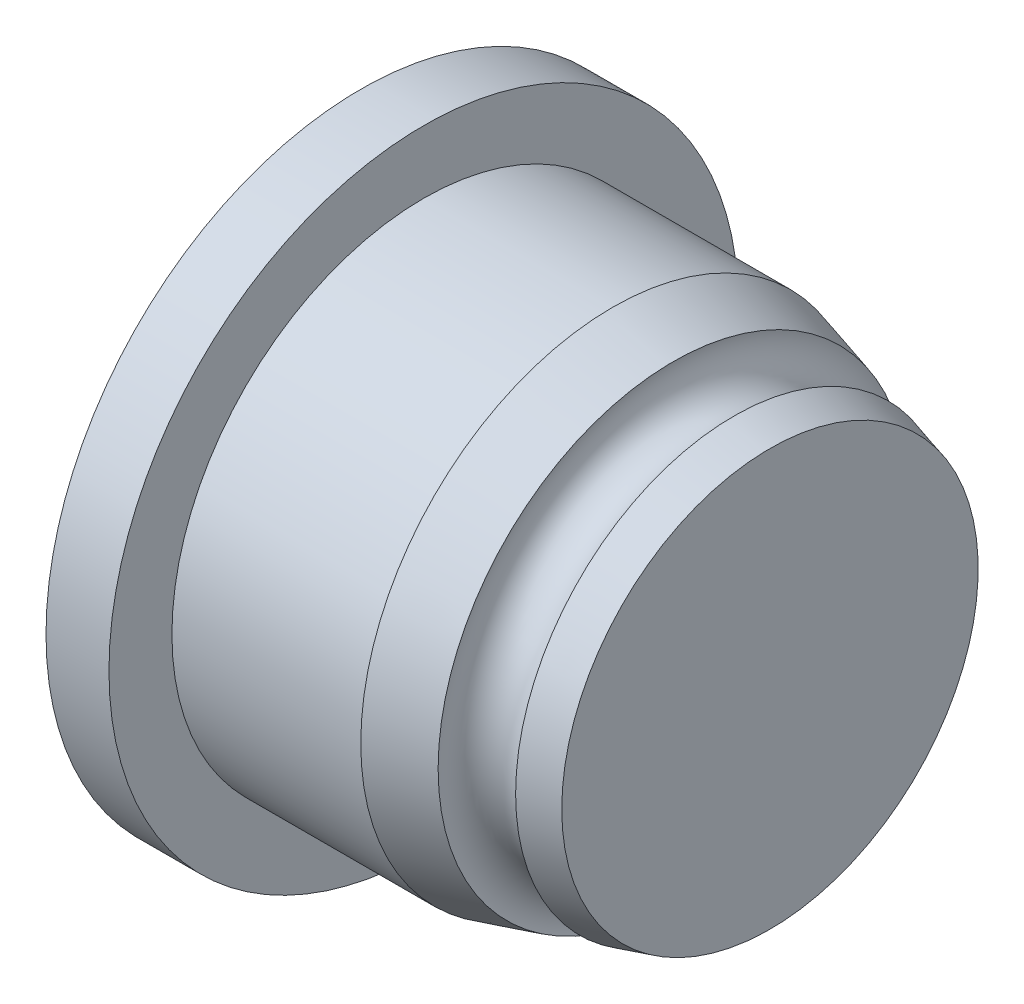
SolidWorks part; units mm, degrees
ref_plane "Front Plane" through (0, 0, 0) normal (0, 0, 1) x (1, 0, 0)
ref_plane "Top Plane" through (0, 0, 0) normal (0, 1, 0) x (1, 0, 0)
ref_plane "Right Plane" through (0, 0, 0) normal (1, 0, 0) x (0, 0, -1)
other "Configuration Table"
sketch "Sketch2" plane through (0, 0, 0) normal (0, 1, 0) x (1, 0, 0)
  line L0 (0, 0) -> (0, 5)
  line L1 (0, 5) -> (1, 5)
  line L2 (1, 5) -> (1, 4)
  line L3 (1, 4) -> (4, 4)
  line L4 (0, 0) -> (6.5, 0)
  line L5 (6.5, 0) -> (6.5, 3.3075)
  line L7 (4, 4) -> (6.5, 3.3075) construction
  line L8 (4, 4) -> (4.9622, 3.7335)
  line L9 (5.926, 3.4665) -> (6.5, 3.3075)
  arc A0 (4.9622, 3.7335) -> (5.926, 3.4665) centre (5.4441, 3.6) ccw
  dimension "D1" = 3
  dimension "D4" = 3.6
  dimension "D2" = 5
  dimension "D3" = 4
  dimension "D5" = 2.5
revolve "Revolve1" add sketch "Sketch2" angle 360 about L4
sketch "Sketch3" plane through (0, 0, 0) normal (-1, 0, 0) x (0, 0, 1)
  circle A0 centre (0, 0) radius 1.75
extrude "Boss-Extrude1" add sketch "Sketch3" against normal blind 4
sketch "Sketch4" plane through (0, 0, 0) normal (-1, 0, 0) x (0, 0, 1)
  circle A0 centre (0, 0) radius 2.55
extrude "Cut-Extrude1" cut sketch "Sketch4" against normal blind 5 and the other way through all
